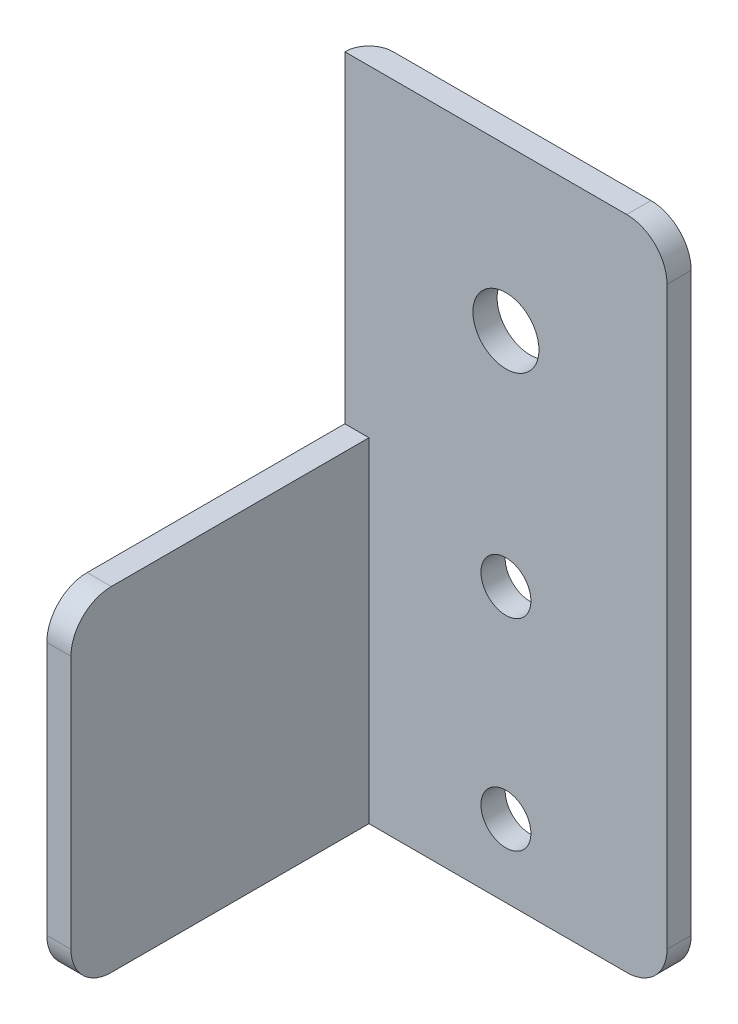
SolidWorks part; units mm, degrees
ref_plane "Front" through (0, 0, 0) normal (0, 0, 1) x (1, 0, 0)
ref_plane "Top" through (0, 0, 0) normal (0, 1, 0) x (1, 0, 0)
ref_plane "Right" through (0, 0, 0) normal (1, 0, 0) x (0, 0, -1)
sketch "Sketch1" plane through (0, 0, 0) normal (0, 1, 0) x (1, 0, 0)
  line L0 (0, -3) -> (0, -40)
  line L1 (3, 0) -> (40, 0)
  arc A0 (0, -3) -> (3, 0) centre (3, -3) cw
  point P6 (0, 0)
  dimension "D3" = 3
  dimension "D1" = 40
  dimension "D2" = 40
extrude "Extrude-Thin1" add sketch "Sketch1" along normal blind 81.5 thin
sketch "Sketch2" plane through (3, 0, 0) normal (1, 0, 0) x (0, 0, -1)
  line L0 (-40, 81.5) -> (-40, 0) construction
  line L1 (-3, 41.5) -> (-40, 41.5)
  line L2 (-3, 41.5) -> (-3, 81.5)
  line L3 (-3, 81.5) -> (-40, 81.5)
  line L4 (-40, 41.5) -> (-40, 81.5)
  line L5 (-40, 81.5) -> (-3, 81.5) construction
  dimension "D1" = 40
  dimension "D2" = 37
extrude "Cut-Extrude1" cut sketch "Sketch2" against normal blind 10
sketch "Sketch3" plane through (0, 0, 0) normal (0, 0, -1) x (-1, 0, 0)
  line L1 (-40, 81.5) -> (-40, 0) construction
  line L2 (-3, 81.5) -> (-40, 81.5) construction
  circle A0 centre (-20, 61.5) radius 4.1
  dimension "D1" = 8.2
  dimension "D2" = 20
  dimension "D3" = 20
extrude "Cut-Extrude2" cut sketch "Sketch3" against normal blind 10
sketch "Sketch4" plane through (0, 0, 0) normal (0, 0, -1) x (-1, 0, 0)
  line L0 (-3, 0) -> (-40, 0) construction
  line L1 (-40, 81.5) -> (-40, 0) construction
  circle A0 centre (-20, 9) radius 3.1
  circle A1 centre (-20, 34) radius 3.1
  dimension "D1" = 6.2
  dimension "D2" = 25
  dimension "D3" = 9
  dimension "D4" = 20
extrude "Cut-Extrude3" cut sketch "Sketch4" against normal blind 10
fillet "Fillet1" radius 5 4 edges at (40, 0, 1.5) (40, 81.5, 1.5) (1.5, 41.5, 40) (1.5, 0, 40)
